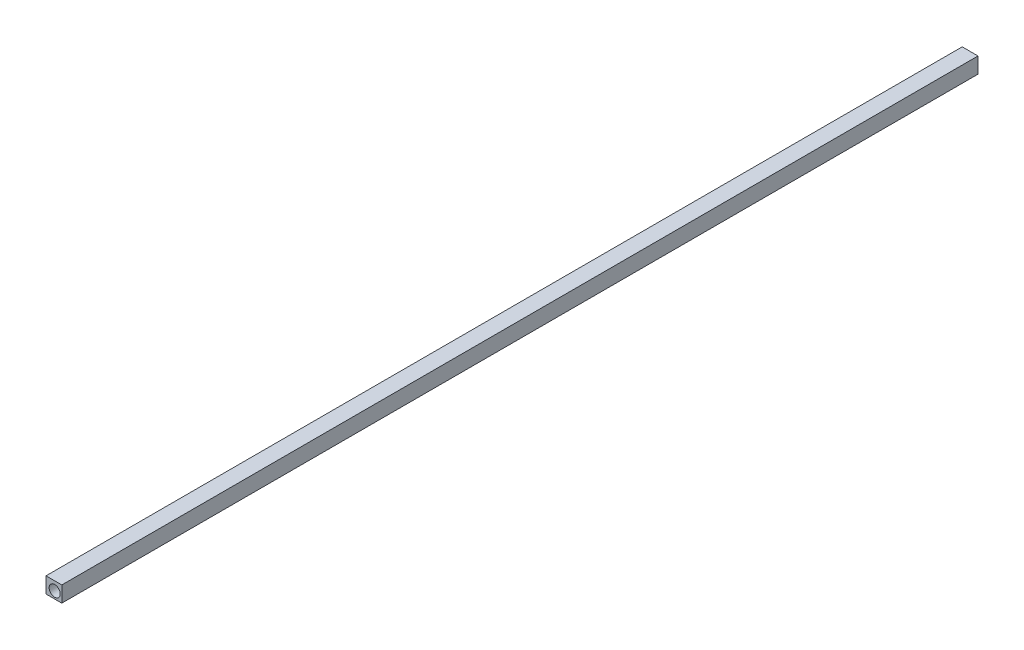
SolidWorks part; units mm, degrees
ref_plane "정면" through (0, 0, 0) normal (0, 0, 1) x (1, 0, 0)
ref_plane "윗면" through (0, 0, 0) normal (0, 1, 0) x (1, 0, 0)
ref_plane "우측면" through (0, 0, 0) normal (1, 0, 0) x (0, 0, -1)
sketch "스케치1" plane through (0, 0, 0) normal (0, 0, 1) x (1, 0, 0)
  line L1 (-5, 5) -> (5, 5)
  line L2 (-5, 5) -> (-5, -5)
  line L3 (-5, -5) -> (5, -5)
  line L4 (5, 5) -> (5, -5)
  line L5 (-5, 5) -> (5, -5) construction
  line L6 (-5, -5) -> (5, 5) construction
  circle A0 centre (0.5, -0.5) radius 3.5
  point P0 (0, 0)
  dimension "D3" = 7
  dimension "D4" = 5.5
  dimension "D1" = 10
  dimension "D2" = 10
  dimension "D5" = 5.5
extrude "보스-돌출1" add sketch "스케치1" along normal blind 580
